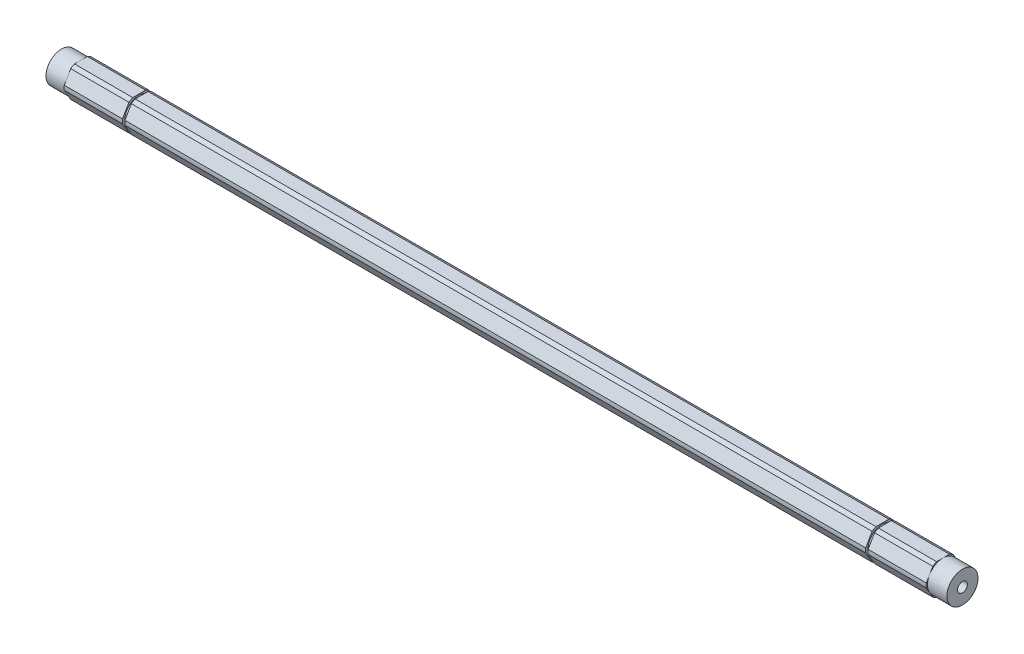
SolidWorks part; units mm, degrees
material "7075-T6 (SN)"
ref_plane "Front Plane" through (0, 0, 0) normal (0, 0, 1) x (1, 0, 0)
ref_plane "Top Plane" through (0, 0, 0) normal (0, 1, 0) x (1, 0, 0)
ref_plane "Right Plane" through (0, 0, 0) normal (1, 0, 0) x (0, 0, -1)
sketch "Sketch1" plane through (0, 0, 0) normal (1, 0, 0) x (0, 0, -1)
  line L1 (7.3323, 0) -> (3.6662, 6.35)
  line L2 (3.6662, 6.35) -> (-3.6662, 6.35)
  line L3 (-3.6662, 6.35) -> (-7.3323, 0)
  line L4 (-7.3323, 0) -> (-3.6662, -6.35)
  line L5 (-3.6662, -6.35) -> (3.6662, -6.35)
  line L6 (3.6662, -6.35) -> (7.3323, 0)
  circle A0 centre (0, 0) radius 6.875
  circle A1 centre (0, 0) radius 2.0193
  circle A2 centre (0, 0) radius 6.35 construction
  dimension "D1" = 12.7
  dimension "D2" = 13.75
  dimension "D3" = 4.0386
extrude "Boss-Extrude1" add sketch "Sketch1" along normal mid plane 368.3 contours L1 A0 L2 L3 L4 L5 L6 A1
sketch "Sketch2" plane through (184.15, 0, 0) normal (1, 0, 0) x (0, 0, -1)
  circle A0 centre (0, 0) radius 6.35
  dimension "D1" = 12.7
extrude "Cut-Extrude-Thin1" cut sketch "Sketch2" against normal blind 7.9375 thin
mirror "Mirror1" about plane through (0, 0, 0) normal (1, 0, 0) of "Cut-Extrude-Thin1"
sketch "Sketch4" plane through (0, 0, 0) normal (0, 0, 1) x (1, 0, 0)
  line L0 (184.15, -6.35) -> (184.15, 6.35) construction
  line L1 (151.4094, 8.6573) -> (152.4, 8.6573)
  line L2 (151.4094, 8.6573) -> (151.4094, 5.8547)
  line L3 (151.4094, 5.8547) -> (152.4, 5.8547)
  line L4 (152.4, 8.6573) -> (152.4, 5.8547)
  line L7 (176.2125, 0) -> (-176.2125, 0) construction
  point P6 (150.3522, 4.049)
  point P7 (152.4, 6.35)
  point P9 (152.4, 8.6573)
  point P10 (150.4171, 3.4653)
  dimension "D1" = 31.75
  dimension "D2" = 0.9906
  dimension "D3" = 5.8547
revolve "Cut-Revolve7" cut sketch "Sketch4" angle 360 about axis through (184.15, 0, 0) along (-1, 0, 0)
mirror "Mirror2" about plane through (0, 0, 0) normal (1, 0, 0) of "Cut-Revolve7"
equation "\"D2@Sketch1\"=13.75mm"
